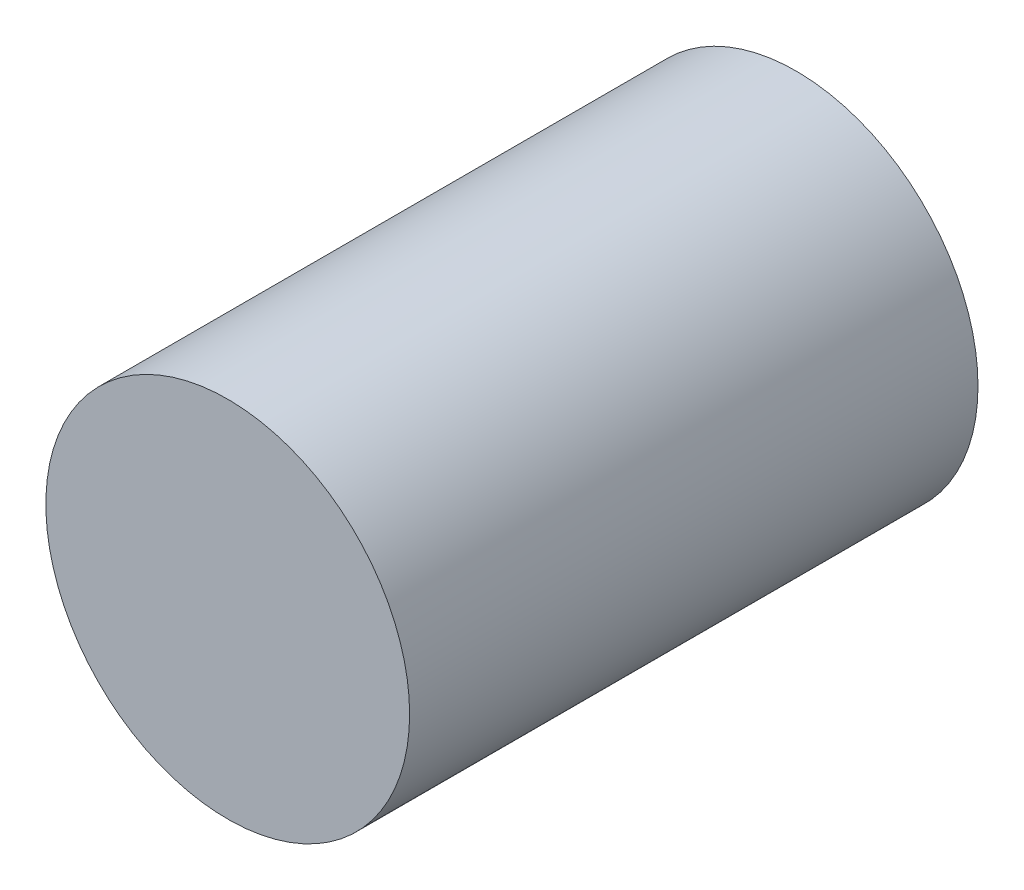
SolidWorks part; units mm, degrees
ref_plane "Alzado" through (0, 0, 0) normal (0, 0, 1) x (1, 0, 0)
ref_plane "Planta" through (0, 0, 0) normal (0, 1, 0) x (1, 0, 0)
ref_plane "Vista lateral" through (0, 0, 0) normal (1, 0, 0) x (0, 0, -1)
sketch "Croquis1" plane through (0, 0, 0) normal (0, 0, 1) x (1, 0, 0)
  circle A0 centre (0, 0) radius 8
  dimension "D1" = 16
extrude "Saliente-Extruir1" add sketch "Croquis1" along normal blind 25
